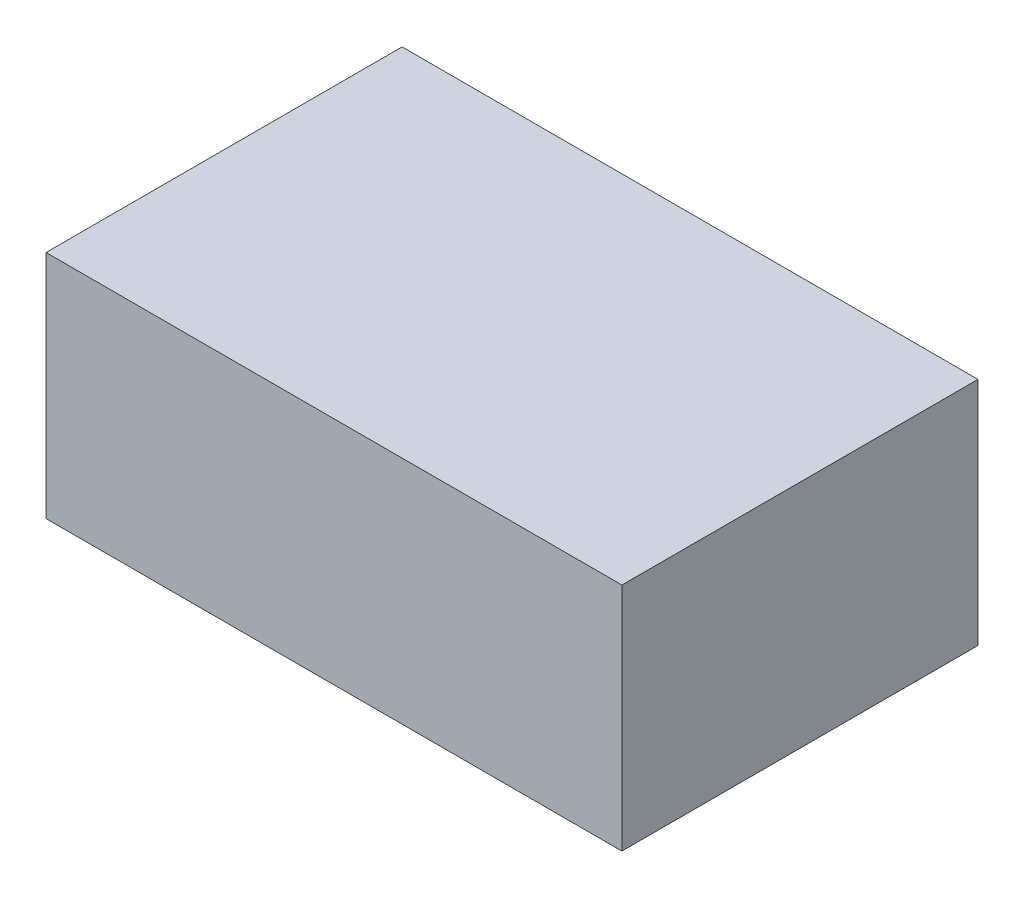
SolidWorks part; units mm, degrees
material "Cast Alloy Steel"
ref_plane "Front Plane" through (0, 0, 0) normal (0, 0, 1) x (1, 0, 0)
ref_plane "Top Plane" through (0, 0, 0) normal (0, 1, 0) x (1, 0, 0)
ref_plane "Right Plane" through (0, 0, 0) normal (1, 0, 0) x (0, 0, -1)
sketch "Sketch1" plane through (0, 0, 0) normal (0, 1, 0) x (1, 0, 0)
  line L1 (0, 98.1221) -> (158.6855, 98.1221)
  line L2 (0, 98.1221) -> (0, 0)
  line L3 (0, 0) -> (158.6855, 0)
  line L4 (158.6855, 98.1221) -> (158.6855, 0)
extrude "Boss-Extrude1" add sketch "Sketch1" along normal blind 63.5
